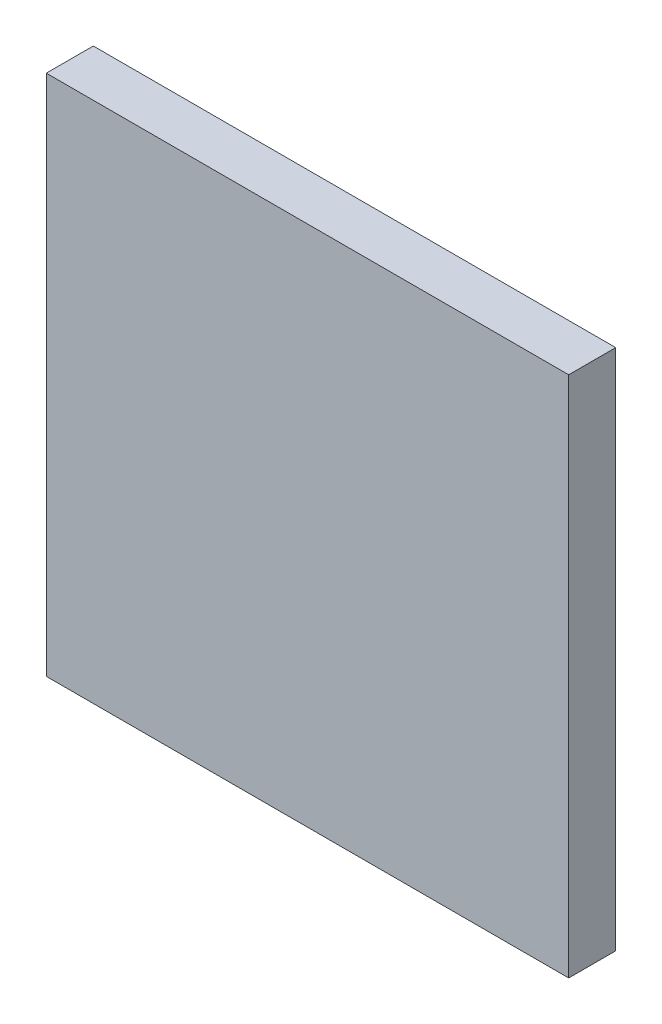
SolidWorks part; units mm, degrees
ref_plane "前视基准面" through (0, 0, 0) normal (0, 0, 1) x (1, 0, 0)
ref_plane "上视基准面" through (0, 0, 0) normal (0, 1, 0) x (1, 0, 0)
ref_plane "右视基准面" through (0, 0, 0) normal (1, 0, 0) x (0, 0, -1)
sketch "草图1" plane through (0, 0, 0) normal (0, 0, 1) x (1, 0, 0)
  line L1 (-5, -5) -> (5, -5)
  line L2 (-5, -5) -> (-5, 5)
  line L3 (-5, 5) -> (5, 5)
  line L4 (5, -5) -> (5, 5)
  line L5 (-5, -5) -> (5, 5) construction
  line L6 (-5, 5) -> (5, -5) construction
  point P0 (0, 0)
  dimension "D1" = 10
  dimension "D2" = 10
extrude "凸台-拉伸1" add sketch "草图1" along normal blind 0.9
